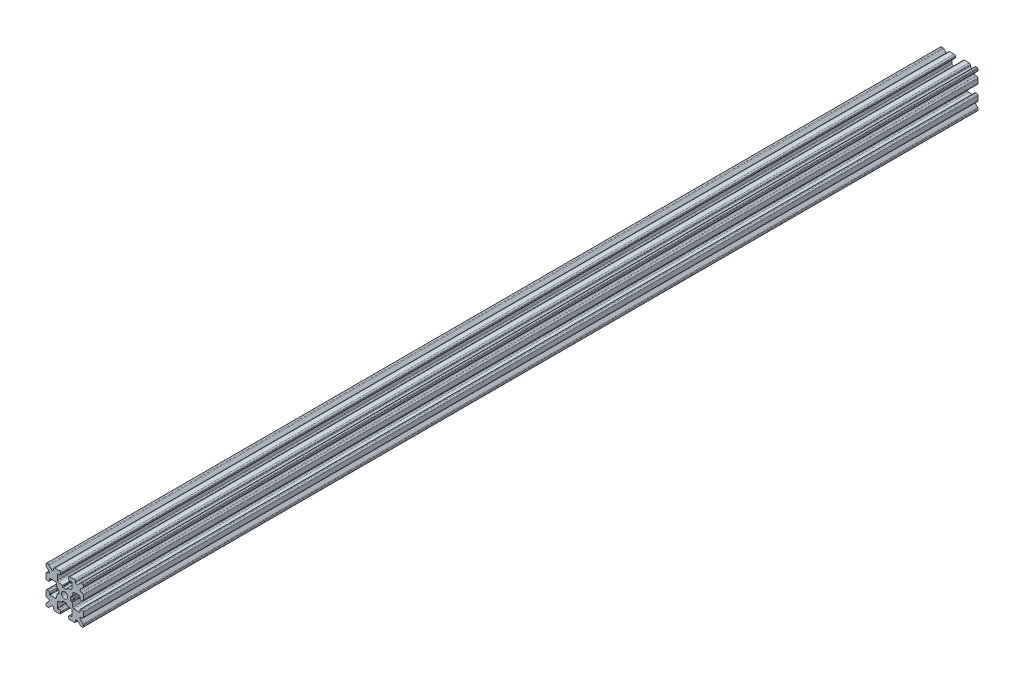
SolidWorks part; units mm, degrees
material "1060 Alloy"
ref_plane "Front Plane" through (0, 0, 0) normal (0, 0, 1) x (1, 0, 0)
ref_plane "Top Plane" through (0, 0, 0) normal (0, 1, 0) x (1, 0, 0)
ref_plane "Right Plane" through (0, 0, 0) normal (1, 0, 0) x (0, 0, -1)
sketch "Sketch1" plane through (0, 0, 0) normal (0, 0, 1) x (1, 0, 0)
  line L1 (-7.5, -7.5) -> (7.5, -7.5)
  line L2 (-7.5, -7.5) -> (-7.5, 7.5)
  line L3 (-7.5, 7.5) -> (7.5, 7.5)
  line L4 (7.5, -7.5) -> (7.5, 7.5)
  line L5 (-7.5, -7.5) -> (7.5, 7.5) construction
  line L6 (-7.5, 7.5) -> (7.5, -7.5) construction
  circle A0 centre (0, 0) radius 1.25
  point P0 (0, 0)
  dimension "D2" = 2.5
  dimension "D1" = 15
extrude "Boss-Extrude1" add sketch "Sketch1" along normal mid plane 360
fillet "Fillet1" radius 0.25 4 edges at (7.5, -7.5, 0) (-7.5, -7.5, 0) (7.5, 7.5, 0) (-7.5, 7.5, 0)
sketch "Sketch2" plane through (0, 0, 180) normal (0, 0, 1) x (1, 0, 0)
  line L0 (-7.5, 7.25) -> (-7.5, -7.25) construction
  line L1 (-7.5, 1.6) -> (-6.1, 1.6)
  line L2 (-7.5, 1.6) -> (-7.5, -1.6)
  line L3 (-7.5, -1.6) -> (-6.1, -1.6)
  line L4 (-6.1, 1.6) -> (-6.1, 2.9)
  line L5 (0, 0) -> (-12.1036, 0) construction
  line L6 (-6.1, -2.9) -> (-3.4, -2.9)
  line L7 (0, 0) -> (-7.25, 7.25) construction
  line L8 (-6.1, 2.9) -> (-3.4, 2.9)
  line L9 (-3.4, -2.9) -> (-3.4, 2.9)
  line L10 (55, 0) -> (-55, 0) construction
  line L11 (-6.1, -2.9) -> (-6.1, -1.6)
  line L12 (2.9, 6.1) -> (1.6, 6.1)
  line L13 (2.9, 3.4) -> (-2.9, 3.4)
  line L14 (-2.9, 6.1) -> (-2.9, 3.4)
  line L15 (2.9, 6.1) -> (2.9, 3.4)
  line L16 (-1.6, 6.1) -> (-2.9, 6.1)
  line L17 (1.6, 7.5) -> (1.6, 6.1)
  line L18 (-1.6, 7.5) -> (1.6, 7.5)
  line L19 (-1.6, 7.5) -> (-1.6, 6.1)
  line L20 (-1.6, -7.5) -> (-1.6, -6.1)
  line L21 (-1.6, -7.5) -> (1.6, -7.5)
  line L22 (1.6, -7.5) -> (1.6, -6.1)
  line L23 (-1.6, -6.1) -> (-2.9, -6.1)
  line L24 (2.9, -6.1) -> (2.9, -3.4)
  line L25 (-2.9, -6.1) -> (-2.9, -3.4)
  line L26 (2.9, -3.4) -> (-2.9, -3.4)
  line L27 (2.9, -6.1) -> (1.6, -6.1)
  line L28 (6.1, -2.9) -> (6.1, -1.6)
  line L29 (3.4, -2.9) -> (3.4, 2.9)
  line L30 (6.1, 2.9) -> (3.4, 2.9)
  line L31 (6.1, -2.9) -> (3.4, -2.9)
  line L32 (6.1, 1.6) -> (6.1, 2.9)
  line L33 (7.5, -1.6) -> (6.1, -1.6)
  line L34 (7.5, 1.6) -> (7.5, -1.6)
  line L35 (7.5, 1.6) -> (6.1, 1.6)
  dimension "D1" = 3.2
  dimension "D2" = 5.8
  dimension "D3" = 1.4
  dimension "D4" = 2.7
extrude "Cut-Extrude1" cut sketch "Sketch2" against normal through all
sketch "Sketch4" plane through (0, 0, 180) normal (0, 0, 1) x (1, 0, 0)
  line L0 (-3.4, 2.9) -> (-2.75, 0)
  line L1 (55, 0) -> (-55, 0) construction
  line L2 (-2.75, 0) -> (-3.4, -2.9)
  line L3 (-3.4, -2.9) -> (-3.4, 2.9) construction
  line L4 (-3.4, 2.9) -> (-3.4, -2.9)
  line L5 (-2.9, 3.4) -> (0, 2.75)
  line L6 (0, 2.75) -> (2.9, 3.4)
  line L7 (2.9, 3.4) -> (-2.9, 3.4)
  line L8 (3.4, 2.9) -> (2.75, 0)
  line L9 (2.75, 0) -> (3.4, -2.9)
  line L10 (3.4, -2.9) -> (3.4, 2.9)
  line L11 (-2.9, -3.4) -> (0, -2.75)
  line L12 (0, -2.75) -> (2.9, -3.4)
  line L13 (2.9, -3.4) -> (-2.9, -3.4)
  circle A2 centre (0, 0) radius 2.75
  circle A3 centre (0, 0) radius 2.75 construction
  dimension "D1" = 1.5
extrude "Cut-Extrude3" cut sketch "Sketch4" against normal through all
fillet "Fillet3" radius 0.5 16 edges at (-6.1, -1.6, 0) (-7.5, -1.6, 0) (-6.1, 1.6, 0) (-7.5, 1.6, 0) (-1.6, -7.5, 0) (-1.6, -6.1, 0) (1.6, -7.5, 0) (1.6, -6.1, 0) (6.1, -1.6, 0) (7.5, -1.6, 0) (7.5, 1.6, 0) (6.1, 1.6, 0) (1.6, 7.5, 0) (1.6, 6.1, 0) (-1.6, 7.5, 0) (-1.6, 6.1, 0)
fillet "Fillet4" radius 0.5 8 edges at (-3.4, 2.9, 0) (-3.4, -2.9, 0) (2.9, -3.4, 0) (-2.9, -3.4, 0) (3.4, -2.9, 0) (3.4, 2.9, 0) (-2.9, 3.4, 0) (2.9, 3.4, 0)
fillet "Fillet5" radius 3 4 edges at (0, -2.75, 0) (2.75, 0, 0) (-2.75, 0, 0) (0, 2.75, 0)
fillet "Fillet6" radius 0.2 8 edges at (-2.9, -6.1, 0) (2.9, -6.1, 0) (6.1, -2.9, 0) (6.1, 2.9, 0) (2.9, 6.1, 0) (-2.9, 6.1, 0) (-6.1, -2.9, 0) (-6.1, 2.9, 0)
sketch "Sketch5" plane through (0, 0, 180) normal (0, 0, 1) x (1, 0, 0)
  line L0 (0, 0) -> (-7.25, 7.25) construction
  line L1 (-7.5, 6.4393) -> (-5.4607, 4.4)
  line L2 (-6.4393, 7.5) -> (-4.4, 5.4607)
  line L3 (-7.5, 4.4) -> (-5.4607, 4.4)
  line L4 (-3.8003, 2.9) -> (-5.9, 2.9) construction
  line L5 (0, 0) -> (-12.1819, 0) construction
  line L6 (-4.4, 7.5) -> (-4.4, 5.4607)
  line L7 (-2.9, 5.9) -> (-2.9, 3.8003) construction
  line L8 (-7.5, 6.4393) -> (-7.5, 4.4)
  line L9 (-7.5, 7.25) -> (-7.5, 2.1) construction
  line L10 (2.1, -7.5) -> (7.25, -7.5) construction
  line L11 (7.5, -7.25) -> (7.5, -2.1) construction
  line L12 (7.25, 7.5) -> (2.1, 7.5) construction
  line L13 (-2.1, 7.5) -> (-7.25, 7.5) construction
  line L14 (-4.4, 7.5) -> (-6.4393, 7.5)
  line L16 (55, 0) -> (-55, 0) construction
  line L17 (0, 0) -> (0, 10.993) construction
  line L18 (0, -54.6431) -> (0, 54.6431) construction
  line L20 (4.4, 7.5) -> (6.4393, 7.5)
  line L22 (7.5, 6.4393) -> (7.5, 4.4)
  line L23 (4.4, 7.5) -> (4.4, 5.4607)
  line L24 (7.5, 4.4) -> (5.4607, 4.4)
  line L25 (6.4393, 7.5) -> (4.4, 5.4607)
  line L26 (7.5, 6.4393) -> (5.4607, 4.4)
  line L27 (7.5, -6.4393) -> (5.4607, -4.4)
  line L28 (6.4393, -7.5) -> (4.4, -5.4607)
  line L29 (7.5, -4.4) -> (5.4607, -4.4)
  line L30 (4.4, -7.5) -> (4.4, -5.4607)
  line L31 (7.5, -6.4393) -> (7.5, -4.4)
  line L33 (4.4, -7.5) -> (6.4393, -7.5)
  line L36 (-4.4, -7.5) -> (-6.4393, -7.5)
  line L38 (-7.5, -6.4393) -> (-7.5, -4.4)
  line L39 (-4.4, -7.5) -> (-4.4, -5.4607)
  line L40 (-7.5, -4.4) -> (-5.4607, -4.4)
  line L41 (-6.4393, -7.5) -> (-4.4, -5.4607)
  line L42 (-7.5, -6.4393) -> (-5.4607, -4.4)
  dimension "D1" = 1.5
  dimension "D2" = 1.5
  dimension "D3" = 1.5
extrude "Cut-Extrude4" cut sketch "Sketch5" against normal through all
fillet "Fillet8" radius 0.5 24 edges at (-5.4607, 4.4, 0) (-7.5, 4.4, 0) (-5.4607, -4.4, 0) (-7.5, -4.4, 0) (-4.4, -7.5, 0) (-4.4, -5.4607, 0) (4.4, -7.5, 0) (4.4, -5.4607, 0) (5.4607, -4.4, 0) (7.5, -4.4, 0) (7.5, 4.4, 0) (5.4607, 4.4, 0) (4.4, 5.4607, 0) (4.4, 7.5, 0) (-4.4, 5.4607, 0) (-4.4, 7.5, 0) (-6.4393, 7.5, 0) (-7.5, 6.4393, 0) (6.4393, 7.5, 0) (7.5, 6.4393, 0) (6.4393, -7.5, 0) (7.5, -6.4393, 0) (-6.4393, -7.5, 0) (-7.5, -6.4393, 0)
sketch "Sketch6" plane through (0, 0, 180) normal (0, 0, 1) x (1, 0, 0)
  line L0 (0, 0) -> (0, 11.013) construction
  line L1 (0.6561, 2.8971) -> (2.1235, 2.8971) construction
  line L2 (0, -54.6431) -> (0, 54.6431) construction
  line L3 (0, 0) -> (7.25, 7.25) construction
  line L4 (7.5, 0.8255) -> (7.5, -0.8255)
  line L5 (2.3471, 0.8255) -> (7.5, 0.8255)
  line L6 (0, 0) -> (12.4016, 0) construction
  line L7 (0.8255, -7.5) -> (-0.8255, -7.5)
  line L8 (2.3471, -0.8255) -> (2.3471, 0.8255)
  line L9 (0.8255, -2.3471) -> (0.8255, -7.5)
  line L10 (7.5, -0.8255) -> (2.3471, -0.8255)
  line L11 (-7.5, -0.8255) -> (-2.3471, -0.8255)
  line L12 (-2.3471, -0.8255) -> (-2.3471, 0.8255)
  line L13 (-0.8255, -2.3471) -> (0.8255, -2.3471)
  line L14 (-0.8255, 7.5) -> (-0.8255, 2.3471)
  line L15 (-0.8255, 2.3471) -> (0.8255, 2.3471)
  line L16 (-0.8255, -7.5) -> (-0.8255, -2.3471)
  line L17 (0.8255, 2.3471) -> (0.8255, 7.5)
  line L18 (0.8255, 7.5) -> (-0.8255, 7.5)
  line L19 (3.9, 7.5) -> (2.1, 7.5) construction
  line L20 (-2.3471, 0.8255) -> (-7.5, 0.8255)
  line L21 (-7.5, 0.8255) -> (-7.5, -0.8255)
  point P5 (0, -2.5973)
  point P7 (0, 2.5973)
  dimension "D3" = 0.55
  dimension "D1" = 1.651
extrude "Cut-Extrude5" cut sketch "Sketch6" against normal through all
fillet "Fillet10" radius 0.2 16 edges at (-2.935, 0.8255, 0) (-2.935, -0.8255, 0) (2.935, -0.8255, 0) (2.935, 0.8255, 0) (0.8255, 2.935, 0) (-0.8255, 2.935, 0) (-2.3471, 0.8255, 0) (-2.3471, -0.8255, 0) (0.8255, 2.3471, 0) (-0.8255, 2.3471, 0) (2.3471, 0.8255, 0) (2.3471, -0.8255, 0) (0.8255, -2.935, 0) (0.8255, -2.3471, 0) (-0.8255, -2.3471, 0) (-0.8255, -2.935, 0)
